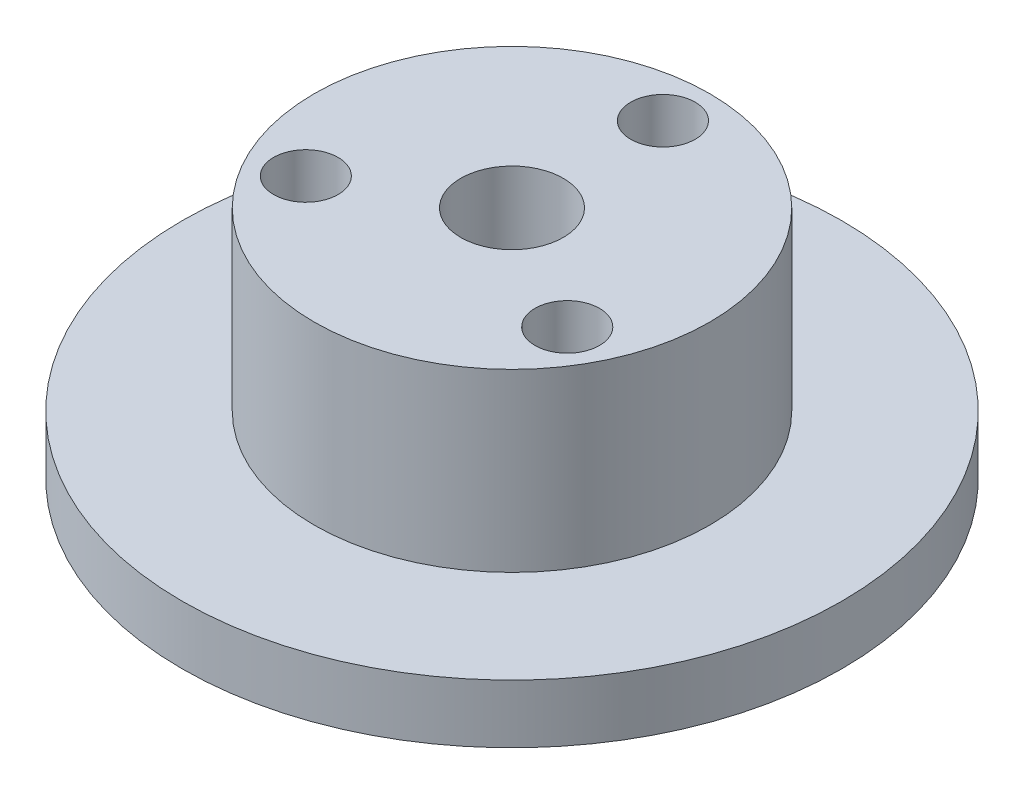
SolidWorks part; units mm, degrees
ref_plane "前视基准面" through (0, 0, 0) normal (0, 0, 1) x (1, 0, 0)
ref_plane "上视基准面" through (0, 0, 0) normal (0, 1, 0) x (1, 0, 0)
ref_plane "右视基准面" through (0, 0, 0) normal (1, 0, 0) x (0, 0, -1)
sketch "草图1" plane through (0, 0, 0) normal (0, 1, 0) x (1, 0, 0)
  circle A0 centre (0, 0) radius 11.25
  dimension "D1" = 22.5
extrude "凸台-拉伸1" add sketch "草图1" along normal blind 8
sketch "草图3" plane through (0, 8, 0) normal (0, 1, 0) x (1, 0, 0)
  circle A0 centre (0, 0) radius 6.75
  circle A2 centre (0, 0) radius 11.25
  circle A3 centre (0, 0) radius 11.25
  dimension "D1" = 13.5
  dimension "D2" = 0
extrude "切除-拉伸1" cut sketch "草图3" against normal blind 6
sketch "草图4" plane through (0, 8, 0) normal (0, 1, 0) x (1, 0, 0)
  line L0 (0, 0) -> (0, 11.25) construction
  circle A0 centre (0, 0) radius 1.75
  circle A1 centre (0, 5.15) radius 1.1
  circle A2 centre (0, 0) radius 11.25 construction
  circle A3 centre (4.46, -2.575) radius 1.1
  circle A4 centre (-4.46, -2.575) radius 1.1
  point P15 (0, 0)
  dimension "D1" = 3.5
  dimension "D2" = 5.15
  dimension "D3" = 2.2
  dimension "D4" = 3
extrude "切除-拉伸2" cut sketch "草图4" against normal through all
